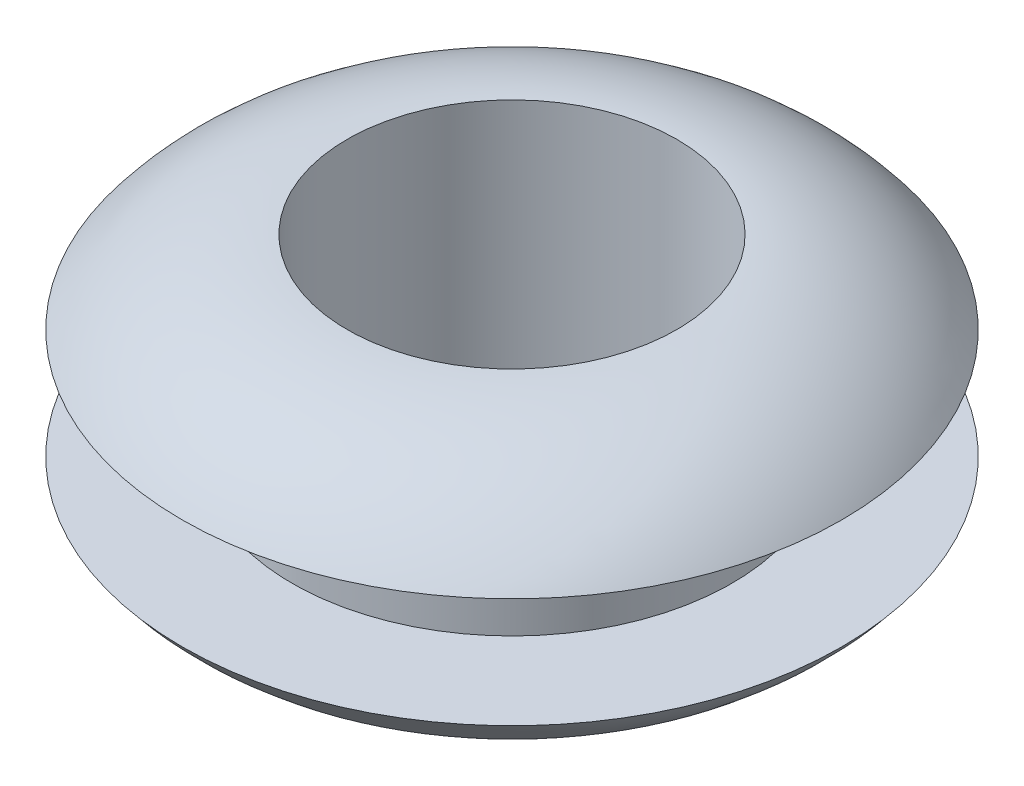
SolidWorks part; units mm, degrees
ref_plane "Спереди" through (0, 0, 0) normal (0, 0, 1) x (1, 0, 0)
ref_plane "Сверху" through (0, 0, 0) normal (0, 1, 0) x (1, 0, 0)
ref_plane "Справа" through (0, 0, 0) normal (1, 0, 0) x (0, 0, -1)
sketch "Эскиз1" plane through (0, 0, 0) normal (0, 0, 1) x (1, 0, 0)
  line L0 (-3, -2.5) -> (-3, 2.5)
  line L1 (-6, 1) -> (-4, 1)
  line L2 (-4, 1) -> (-4, -1)
  line L3 (-4, 0) -> (-3, 0) construction
  line L4 (-6, -1) -> (-4, -1)
  line L5 (0, 0) -> (0, 2.5) construction
  arc A0 (-3, 2.5) -> (-6, 1) centre (-2.9802, -1.2896) ccw
  arc A1 (-3, -2.5) -> (-6, -1) centre (-2.9802, 1.2896) cw
  dimension "D1" = 4
  dimension "D2" = 3
  dimension "D3" = 2.5
  dimension "D4" = 1
  dimension "D5" = 6
revolve "Повернуть1" add sketch "Эскиз1" angle 360 about L5
